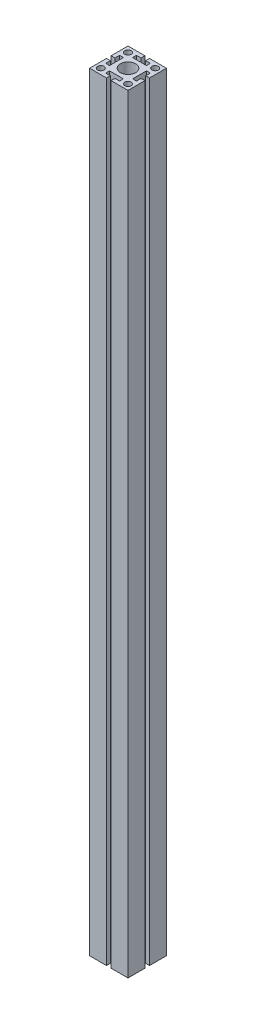
SolidWorks part; units mm, degrees
ref_plane "Front Plane" through (0, 0, 0) normal (0, 0, 1) x (1, 0, 0)
ref_plane "Top Plane" through (0, 0, 0) normal (0, 1, 0) x (1, 0, 0)
ref_plane "Right Plane" through (0, 0, 0) normal (1, 0, 0) x (0, 0, -1)
sketch "Sketch1" plane through (0, 0, 0) normal (0, 1, 0) x (1, 0, 0)
  line L1 (-25, -3) -> (-25, -25)
  line L6 (9, 20) -> (9, 15)
  line L7 (9, 20) -> (3, 20)
  line L8 (9, 15) -> (-9, 15)
  line L9 (3, 20) -> (3, 25)
  line L10 (-3, 25) -> (-25, 25)
  line L11 (-25, 25) -> (-25, 3)
  line L12 (-25, -25) -> (-3, -25)
  line L13 (25, -25) -> (25, -3)
  line L14 (3, 25) -> (25, 25)
  line L15 (-3, 20) -> (-3, 25)
  line L16 (-9, 20) -> (-9, 15)
  line L17 (3, -25) -> (25, -25)
  line L18 (25, 3) -> (25, 25)
  line L19 (-3, 20) -> (-9, 20)
  line L21 (-20, 9) -> (-15, 9)
  line L22 (-20, 9) -> (-20, 3)
  line L24 (-15, 9) -> (-15, -9)
  line L27 (-20, 3) -> (-25, 3)
  line L28 (20, -9) -> (15, -9)
  line L29 (20, -9) -> (20, -3)
  line L30 (15, -9) -> (15, 9)
  line L31 (20, -3) -> (25, -3)
  line L32 (20, 3) -> (25, 3)
  line L33 (-20, -3) -> (-25, -3)
  line L34 (20, 9) -> (15, 9)
  line L35 (20, 3) -> (20, 9)
  line L40 (-20, -9) -> (-15, -9)
  line L41 (-20, -3) -> (-20, -9)
  line L42 (-9, -20) -> (-9, -15)
  line L43 (-9, -20) -> (-3, -20)
  line L44 (-9, -15) -> (9, -15)
  line L45 (-3, -20) -> (-3, -25)
  line L46 (3, -20) -> (3, -25)
  line L47 (9, -20) -> (9, -15)
  line L48 (3, -20) -> (9, -20)
  circle A0 centre (0, 0) radius 10
  circle A1 centre (-17.6777, 17.6777) radius 4.1387
  circle A2 centre (17.6777, 17.6777) radius 4.1387
  circle A3 centre (17.6777, -17.6777) radius 4.1387
  circle A4 centre (-17.6777, -17.6777) radius 4.1387
  point P44 (0, 0)
  point P46 (0, 0)
  dimension "D1" = 4
extrude "Boss-Extrude1" add sketch "Sketch1" along normal blind 1000
